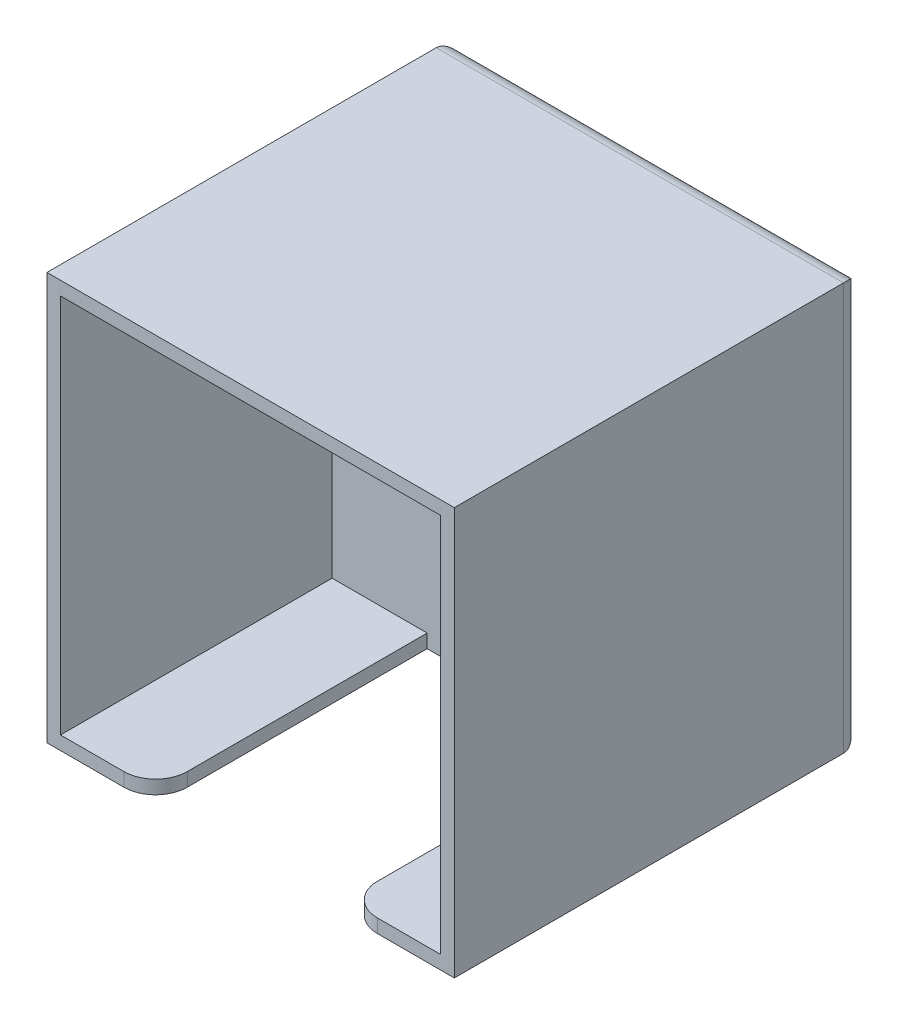
SolidWorks part; units mm, degrees
ref_plane "前视基准面" through (0, 0, 0) normal (0, 0, 1) x (1, 0, 0)
ref_plane "上视基准面" through (0, 0, 0) normal (0, 1, 0) x (1, 0, 0)
ref_plane "右视基准面" through (0, 0, 0) normal (1, 0, 0) x (0, 0, -1)
other "Configuration Table"
sketch "草图2" plane through (0, 0, 0) normal (0, 0, 1) x (1, 0, 0)
  line L1 (-22.5, -22.5) -> (22.5, -22.5)
  line L2 (-22.5, -22.5) -> (-22.5, 22.5)
  line L3 (-22.5, 22.5) -> (22.5, 22.5)
  line L4 (22.5, -22.5) -> (22.5, 22.5)
  line L5 (-22.5, -22.5) -> (22.5, 22.5) construction
  line L6 (-22.5, 22.5) -> (22.5, -22.5) construction
  point P0 (0, 0)
  dimension "D1" = 45
extrude "凸台-拉伸1" add sketch "草图2" along normal blind 45
sketch "草图3" plane through (0, 0, 45) normal (0, 0, 1) x (1, 0, 0)
  line L2 (-21, -21) -> (21, -21)
  line L3 (-21, -21) -> (-21, 21)
  line L4 (-21, 21) -> (21, 21)
  line L5 (21, -21) -> (21, 21)
  line L6 (-21, -21) -> (21, 21) construction
  line L7 (-21, 21) -> (21, -21) construction
  point P2 (0, 0)
  dimension "D1" = 42
extrude "切除-拉伸1" cut sketch "草图3" against normal blind 30
sketch "草图4" plane through (0, -22.5, 0) normal (0, -1, 0) x (1, 0, 0)
  line L0 (-22.5, 45) -> (22.5, 45) construction
  line L1 (-10.5, 15) -> (10.5, 15)
  line L2 (-10.5, 15) -> (-10.5, 45)
  line L3 (-10.5, 45) -> (10.5, 45)
  line L4 (10.5, 15) -> (10.5, 45)
  line L5 (-10.5, 15) -> (10.5, 45) construction
  line L6 (-10.5, 45) -> (10.5, 15) construction
  line L7 (-22.5, 0) -> (22.5, 0) construction
  line L8 (0, 0) -> (0, 45) construction
  line L9 (22.5, 45) -> (22.5, 0) construction
  point P0 (0, 30)
  point P9 (0, 0)
  point P10 (0, 0)
  dimension "D1" = 15
  dimension "D2" = 12
extrude "切除-拉伸2" cut sketch "草图4" against normal up to next
fillet "圆角2" radius 3.5 2 edges at (-10.5, -21.75, 45) (10.5, -21.75, 45)
fillet "圆角3" radius 2 4 edges at (0, -22.5, 0) (-22.5, 0, 0) (0, 22.5, 0) (22.5, 0, 0)
